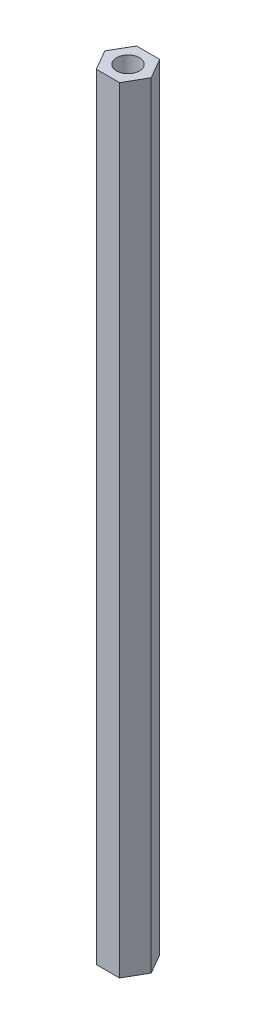
SolidWorks part; units mm, degrees
ref_plane "Front Plane" through (0, 0, 0) normal (0, 0, 1) x (1, 0, 0)
ref_plane "Top Plane" through (0, 0, 0) normal (0, 1, 0) x (1, 0, 0)
ref_plane "Right Plane" through (0, 0, 0) normal (1, 0, 0) x (0, 0, -1)
sketch "Sketch1" plane through (0, 0, 0) normal (0, 1, 0) x (1, 0, 0)
  line L1 (2.0207, 3.5) -> (-2.0207, 3.5)
  line L2 (-2.0207, 3.5) -> (-4.0415, 0)
  line L3 (-4.0415, 0) -> (-2.0207, -3.5)
  line L4 (-2.0207, -3.5) -> (2.0207, -3.5)
  line L5 (2.0207, -3.5) -> (4.0415, 0)
  line L6 (4.0415, 0) -> (2.0207, 3.5)
  circle A0 centre (0, 0) radius 3.5 construction
  circle A1 centre (0, 0) radius 2
  dimension "D1" = 7
  dimension "D2" = 4
extrude "Boss-Extrude1" add sketch "Sketch1" along normal blind 135
